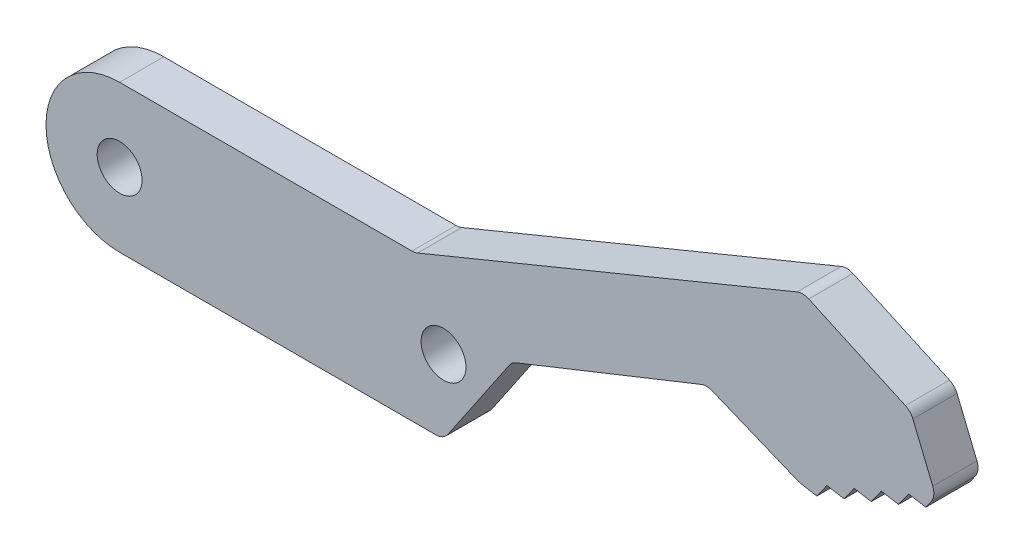
SolidWorks part; units mm, degrees
material "Balsa"
ref_plane "Front Plane" through (0, 0, 0) normal (0, 0, 1) x (1, 0, 0)
ref_plane "Top Plane" through (0, 0, 0) normal (0, 1, 0) x (1, 0, 0)
ref_plane "Right Plane" through (0, 0, 0) normal (1, 0, 0) x (0, 0, -1)
sketch "Sketch1" plane through (0, 0, 0) normal (0, 0, 1) x (1, 0, 0)
  line L0 (0, 0) -> (22, 0) construction
  line L1 (0, 5) -> (22, 5)
  line L2 (0, -5) -> (22, -5)
  line L3 (20.05, 5) -> (23.9914, -4.5863) construction
  line L4 (20.05, 5) -> (51.4959, 17.929) construction
  line L5 (23.9914, -4.5863) -> (55.4373, 8.3426) construction
  line L6 (51.4959, 17.929) -> (55.4373, 8.3426) construction
  line L7 (20.05, 5) -> (46.409, 15.8375)
  line L8 (46.409, 15.8375) -> (53.7261, 12.5046)
  line L9 (53.7261, 12.5046) -> (55.4373, 8.3426)
  line L10 (55.4373, 8.3426) -> (46.1885, 4.54) construction
  line L11 (46.1885, 4.54) -> (39.8718, 7.1258)
  line L12 (39.8718, 7.1258) -> (26.6444, 1.8518)
  line L13 (46.1885, 4.54) -> (47.3529, 4.3376)
  line L14 (47.3529, 4.3376) -> (48.0382, 5.3005)
  line L15 (47.3529, 4.3376) -> (54.752, 7.3797) construction
  line L16 (48.0382, 5.3005) -> (49.2027, 5.0981)
  line L17 (49.2027, 5.0981) -> (49.888, 6.0611)
  line L18 (49.888, 6.0611) -> (51.0524, 5.8587)
  line L19 (51.0524, 5.8587) -> (51.7378, 6.8216)
  line L20 (51.7378, 6.8216) -> (52.9022, 6.6192)
  line L21 (52.9022, 6.6192) -> (53.5875, 7.5821)
  line L22 (53.5875, 7.5821) -> (54.752, 7.3797)
  line L23 (54.752, 7.3797) -> (55.4373, 8.3426)
  line L24 (26.6444, 1.8518) -> (22, -5)
  arc A0 (0, 5) -> (0, -5) centre (0, 0) ccw
  arc A1 (22, -5) -> (22, 5) centre (22, 0) ccw
  circle A2 centre (0, 0) radius 1.525
  circle A3 centre (22, 0) radius 1.525
  point P3 (11, 0)
  dimension "D2" = 10
  dimension "D11" = 3.05
  dimension "D1" = 22
  dimension "D3" = 157.65
  dimension "D4" = 1.95
  dimension "D5" = 34
  dimension "D6" = 136
  dimension "D7" = 10
  dimension "D8" = 4.5
  dimension "D9" = 5.5
  dimension "D10" = 14.24
  dimension "D12" = 2
  dimension "D13" = 0.63
  dimension "D14" = 8
extrude "Boss-Extrude1" add sketch "Sketch1" along normal blind 3 contours L24 A1 L1 A0 L2 A3 A2 | A1 L12 L11 L13 L14 L16 L17 L18 L19 L20 L21 L22 L23 L9 L8 L7 L1
fillet "Fillet1" radius 1 8 edges at (26.6444, 1.8518, 1.5) (22, -5, 1.5) (39.8718, 7.1258, 1.5) (46.1885, 4.54, 1.5) (55.4373, 8.3426, 1.5) (53.7261, 12.5046, 1.5) (46.409, 15.8375, 1.5) (20.05, 5, 1.5)
